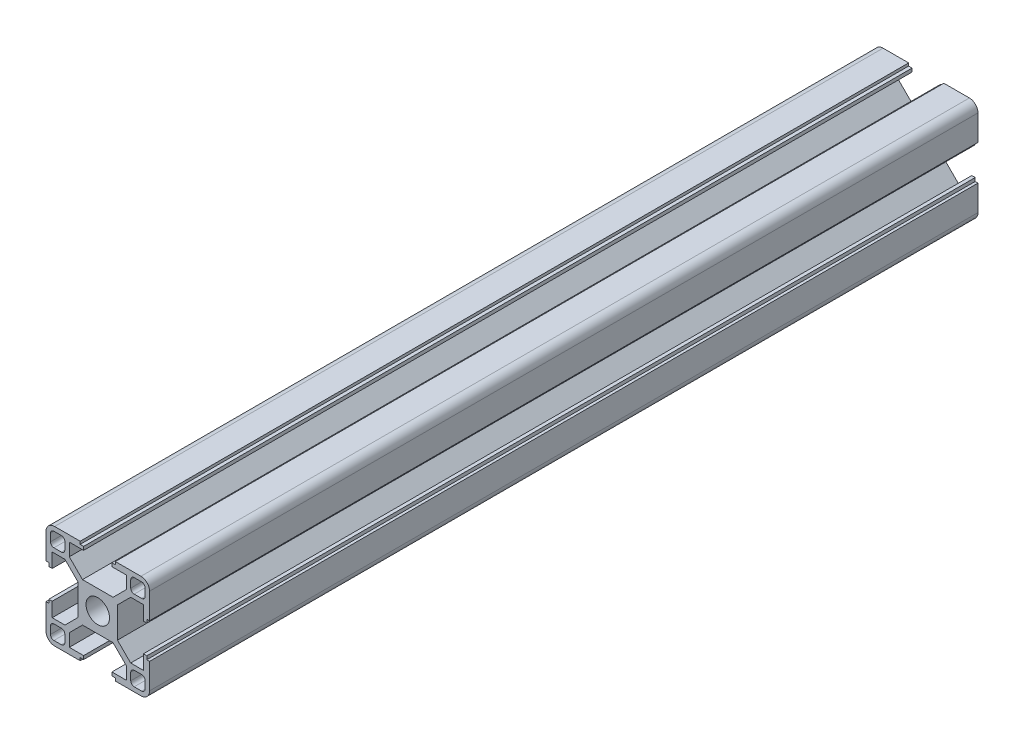
SolidWorks part; units mm, degrees
material "6061-T6 (SS)"
ref_plane "前视基准面" through (0, 0, 0) normal (0, 0, 1) x (1, 0, 0)
ref_plane "上视基准面" through (0, 0, 0) normal (0, 1, 0) x (1, 0, 0)
ref_plane "右视基准面" through (0, 0, 0) normal (1, 0, 0) x (0, 0, -1)
sketch "Sketch1" plane through (0, 0, 0) normal (0, 0, 1) x (1, 0, 0)
  line L0 (-5.1, 15) -> (-5.1, 14.2)
  line L1 (-12.5, -15) -> (12.5, -15)
  line L2 (-15, -12.5) -> (-15, 12.5)
  line L3 (-12.5, 15) -> (12.5, 15)
  line L4 (15, -12.5) -> (15, 12.5)
  line L5 (-15, -15) -> (15, 15) construction
  line L6 (-15, 15) -> (15, -15) construction
  line L7 (-5.1, 14.2) -> (-4.1, 14.2)
  line L8 (-4.1, 14.2) -> (-4.1, 13.2)
  line L9 (-4.1, 13.2) -> (-8.25, 13.2)
  line L10 (-8.25, 13.2) -> (-8.25, 9.5228)
  line L11 (-8.25, 9.5228) -> (-4.4272, 5.7)
  line L12 (-4.4272, 5.7) -> (4.4272, 5.7)
  line L13 (-5.1, 15) -> (5.1, 15)
  line L14 (0, 15) -> (0, 5.7) construction
  line L15 (8.25, 9.5228) -> (4.4272, 5.7)
  line L16 (8.25, 13.2) -> (8.25, 9.5228)
  line L17 (4.1, 13.2) -> (8.25, 13.2)
  line L18 (4.1, 14.2) -> (4.1, 13.2)
  line L19 (5.1, 14.2) -> (4.1, 14.2)
  line L20 (5.1, 15) -> (5.1, 14.2)
  line L21 (15, 5.1) -> (14.2, 5.1)
  line L22 (14.2, 5.1) -> (14.2, 4.1)
  line L23 (14.2, 4.1) -> (13.2, 4.1)
  line L24 (13.2, 4.1) -> (13.2, 8.25)
  line L25 (13.2, 8.25) -> (9.5228, 8.25)
  line L26 (9.5228, 8.25) -> (5.7, 4.4272)
  line L27 (5.7, 4.4272) -> (5.7, -4.4272)
  line L28 (15, 5.1) -> (15, -5.1)
  line L29 (9.5228, -8.25) -> (5.7, -4.4272)
  line L30 (13.2, -8.25) -> (9.5228, -8.25)
  line L31 (13.2, -4.1) -> (13.2, -8.25)
  line L32 (14.2, -4.1) -> (13.2, -4.1)
  line L33 (14.2, -5.1) -> (14.2, -4.1)
  line L34 (15, -5.1) -> (14.2, -5.1)
  line L35 (15, 0) -> (5.7, 0) construction
  line L36 (5.1, -15) -> (5.1, -14.2)
  line L37 (5.1, -14.2) -> (4.1, -14.2)
  line L38 (4.1, -14.2) -> (4.1, -13.2)
  line L39 (4.1, -13.2) -> (8.25, -13.2)
  line L40 (8.25, -13.2) -> (8.25, -9.5228)
  line L41 (8.25, -9.5228) -> (4.4272, -5.7)
  line L42 (4.4272, -5.7) -> (-4.4272, -5.7)
  line L43 (5.1, -15) -> (-5.1, -15)
  line L44 (-8.25, -9.5228) -> (-4.4272, -5.7)
  line L45 (-8.25, -13.2) -> (-8.25, -9.5228)
  line L46 (-4.1, -13.2) -> (-8.25, -13.2)
  line L47 (-4.1, -14.2) -> (-4.1, -13.2)
  line L48 (-5.1, -14.2) -> (-4.1, -14.2)
  line L49 (-5.1, -15) -> (-5.1, -14.2)
  line L50 (0, -15) -> (0, -5.7) construction
  line L51 (-15, -5.1) -> (-14.2, -5.1)
  line L52 (-14.2, -5.1) -> (-14.2, -4.1)
  line L53 (-14.2, -4.1) -> (-13.2, -4.1)
  line L54 (-13.2, -4.1) -> (-13.2, -8.25)
  line L55 (-13.2, -8.25) -> (-9.5228, -8.25)
  line L56 (-9.5228, -8.25) -> (-5.7, -4.4272)
  line L57 (-5.7, -4.4272) -> (-5.7, 4.4272)
  line L58 (-15, -5.1) -> (-15, 5.1)
  line L59 (-9.5228, 8.25) -> (-5.7, 4.4272)
  line L60 (-13.2, 8.25) -> (-9.5228, 8.25)
  line L61 (-13.2, 4.1) -> (-13.2, 8.25)
  line L62 (-14.2, 4.1) -> (-13.2, 4.1)
  line L63 (-14.2, 5.1) -> (-14.2, 4.1)
  line L64 (-15, 5.1) -> (-14.2, 5.1)
  line L65 (-15, 0) -> (-5.7, 0) construction
  line L66 (0, 0) -> (0, 5.7) construction
  circle A0 centre (0, 0) radius 3.4
  arc A1 (-12.5, -15) -> (-15, -12.5) centre (-12.5, -12.5) cw
  arc A2 (12.5, -15) -> (15, -12.5) centre (12.5, -12.5) ccw
  arc A3 (12.5, 15) -> (15, 12.5) centre (12.5, 12.5) cw
  arc A4 (-15, 12.5) -> (-12.5, 15) centre (-12.5, 12.5) cw
  point P0 (0, 0)
  dimension "D3" = 6.8
  dimension "D12" = 2.5
  dimension "D1" = 30
  dimension "D2" = 30
  dimension "D4" = 16.5
  dimension "D5" = 8.2
  dimension "D6" = 10.2
  dimension "D7" = 7.5
  dimension "D9" = 1.8
  dimension "D10" = 1.8
  dimension "D11" = 0.8
  dimension "D8" = 4
extrude "Extrude1" add sketch "Sketch1" along normal blind 240 contours A4 L2 L64 L63 L62 L61 L60 L59 L57 L56 L55 L54 L53 L52 L51 A1 L1 L49 L48 L47 L46 L45 L44 L42 L41 L40 L39 L38 L37 L36 A2 L4 L34 L33 L32 L31 L30 L29 L27 L26 L25 L24 L23 L22 L21 A3 L3 L20
sketch "Sketch2" plane through (0, 0, 240) normal (0, 0, 1) x (1, 0, 0)
  line L0 (13.7, 12.7) -> (13.7, 10.55)
  line L1 (-12.7, 13.7) -> (-10.55, 13.7)
  line L2 (-13.7, 12.7) -> (-13.7, 10.55)
  line L3 (-12.7, 9.55) -> (-10.55, 9.55)
  line L4 (-9.55, 12.7) -> (-9.55, 10.55)
  line L5 (-13.7, 13.7) -> (-9.55, 9.55) construction
  line L6 (-13.7, 9.55) -> (-9.55, 13.7) construction
  line L7 (12.7, 13.7) -> (10.55, 13.7)
  line L8 (9.55, 12.7) -> (9.55, 10.55)
  line L9 (12.7, 9.55) -> (10.55, 9.55)
  line L10 (12.7, -13.7) -> (10.55, -13.7)
  line L11 (13.7, -12.7) -> (13.7, -10.55)
  line L12 (12.7, -9.55) -> (10.55, -9.55)
  line L13 (9.55, -12.7) -> (9.55, -10.55)
  line L14 (-13.7, -12.7) -> (-13.7, -10.55)
  line L15 (-12.7, -13.7) -> (-10.55, -13.7)
  line L16 (-9.55, -12.7) -> (-9.55, -10.55)
  line L17 (-12.7, -9.55) -> (-10.55, -9.55)
  line L18 (0, 0) -> (-9.55, 9.55) construction
  line L19 (-12.5, 15) -> (-5.1, 15) construction
  line L20 (-15, 5.1) -> (-15, 12.5) construction
  line L21 (-13.2, 8.25) -> (-9.5228, 8.25) construction
  line L22 (-8.25, 13.2) -> (-8.25, 9.5228) construction
  arc A0 (-13.7, -12.7) -> (-12.7, -13.7) centre (-12.7, -12.7) ccw
  arc A1 (-10.55, -13.7) -> (-9.55, -12.7) centre (-10.55, -12.7) ccw
  arc A2 (-9.55, -10.55) -> (-10.55, -9.55) centre (-10.55, -10.55) ccw
  arc A3 (-13.7, -10.55) -> (-12.7, -9.55) centre (-12.7, -10.55) cw
  arc A4 (13.7, -10.55) -> (12.7, -9.55) centre (12.7, -10.55) ccw
  arc A5 (12.7, -13.7) -> (13.7, -12.7) centre (12.7, -12.7) ccw
  arc A6 (10.55, -13.7) -> (9.55, -12.7) centre (10.55, -12.7) cw
  arc A7 (10.55, -9.55) -> (9.55, -10.55) centre (10.55, -10.55) ccw
  arc A8 (13.7, 12.7) -> (12.7, 13.7) centre (12.7, 12.7) ccw
  arc A9 (13.7, 10.55) -> (12.7, 9.55) centre (12.7, 10.55) cw
  arc A10 (9.55, 10.55) -> (10.55, 9.55) centre (10.55, 10.55) ccw
  arc A11 (10.55, 13.7) -> (9.55, 12.7) centre (10.55, 12.7) ccw
  arc A12 (-10.55, 13.7) -> (-9.55, 12.7) centre (-10.55, 12.7) cw
  arc A13 (-10.55, 9.55) -> (-9.55, 10.55) centre (-10.55, 10.55) ccw
  arc A14 (-13.7, 10.55) -> (-12.7, 9.55) centre (-12.7, 10.55) ccw
  arc A15 (-12.7, 13.7) -> (-13.7, 12.7) centre (-12.7, 12.7) ccw
  point P0 (-11.625, 11.625)
  dimension "D2" = 1
  dimension "D3" = 1.3
  dimension "D4" = 1.3
  dimension "D5" = 1.3
  dimension "D6" = 1.3
  dimension "D1" = 4
extrude "Extrude2" cut sketch "Sketch2" against normal through all
